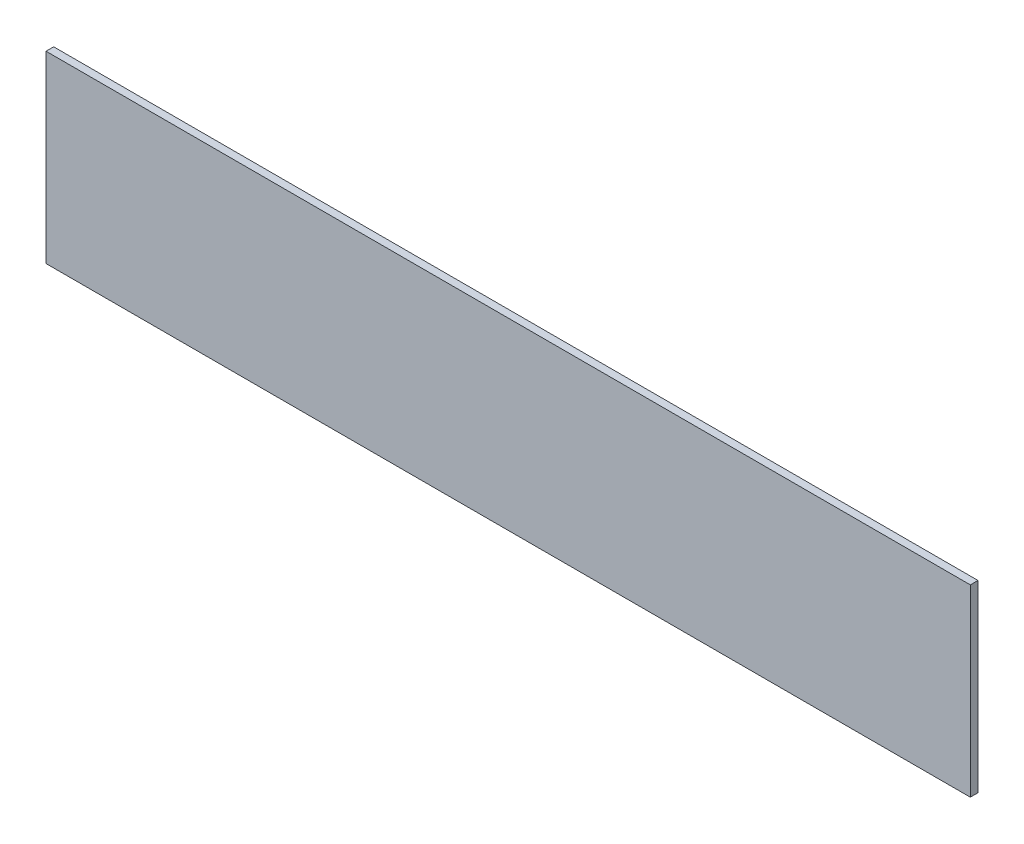
SolidWorks part; units mm, degrees
ref_plane "Front Plane" through (0, 0, 0) normal (0, 0, 1) x (1, 0, 0)
ref_plane "Top Plane" through (0, 0, 0) normal (0, 1, 0) x (1, 0, 0)
ref_plane "Right Plane" through (0, 0, 0) normal (1, 0, 0) x (0, 0, -1)
sketch "Sketch1" plane through (0, 0, 0) normal (0, 0, 1) x (1, 0, 0)
  line L1 (0, 0) -> (383.0066, 0)
  line L2 (0, 0) -> (0, 76.2)
  line L3 (0, 76.2) -> (383.0066, 76.2)
  line L4 (383.0066, 0) -> (383.0066, 76.2)
  dimension "D1" = 383.0066
  dimension "D2" = 76.2
extrude "Boss-Extrude1" add sketch "Sketch1" along normal blind 3.175
